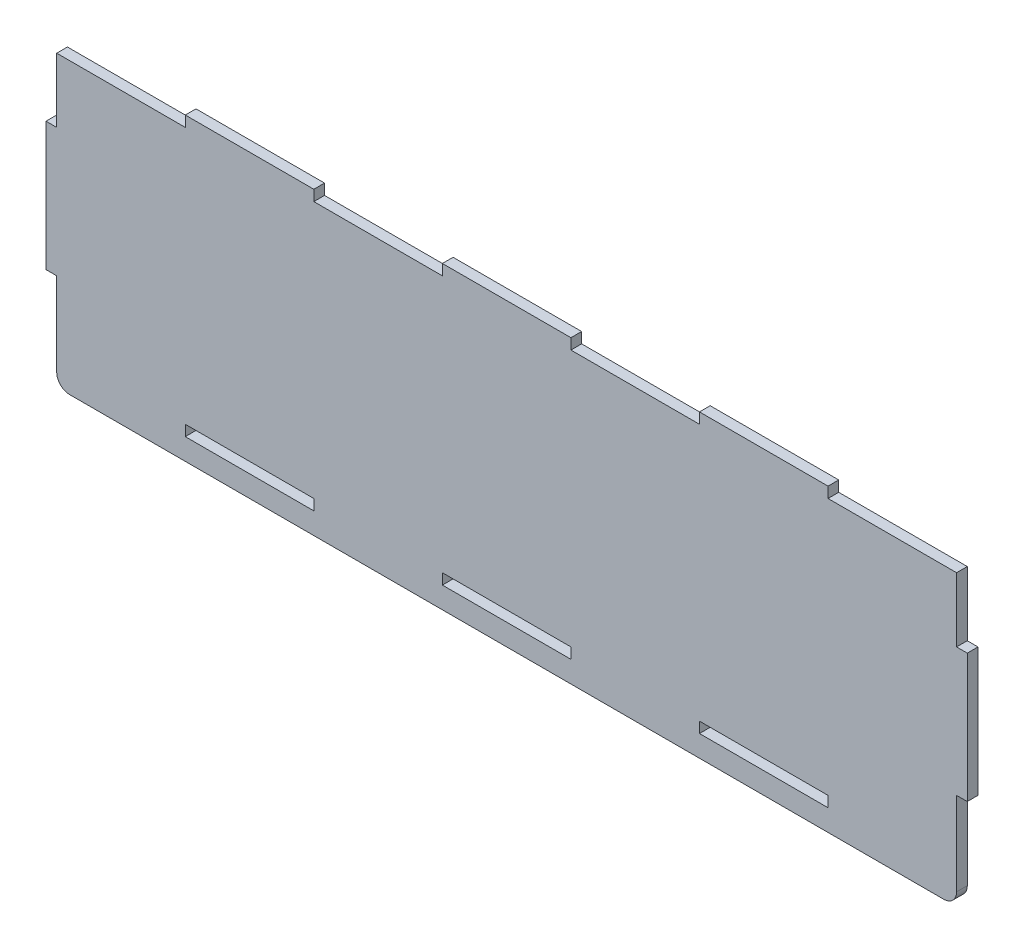
SolidWorks part; units mm, degrees
material "Maple"
ref_plane "Front Plane" through (0, 0, 0) normal (0, 0, 1) x (1, 0, 0)
ref_plane "Top Plane" through (0, 0, 0) normal (0, 1, 0) x (1, 0, 0)
ref_plane "Right Plane" through (0, 0, 0) normal (1, 0, 0) x (0, 0, -1)
sketch "Sketch1" plane through (0, 0, 0) normal (0, 0, 1) x (1, 0, 0)
  line L0 (107.5, 0) -> (-107.5, 0) construction
  line L1 (-107.5, -32.5) -> (107.5, -32.5) construction
  line L2 (-107.5, -32.5) -> (-107.5, 32.5) construction
  line L3 (-107.5, 32.5) -> (107.5, 32.5) construction
  line L4 (107.5, -32.5) -> (107.5, 32.5) construction
  line L5 (-107.5, -32.5) -> (107.5, 32.5) construction
  line L6 (-107.5, 32.5) -> (107.5, -32.5) construction
  line L7 (-107.5, 30) -> (107.5, 30) construction
  line L8 (105, 32.5) -> (105, -32.5) construction
  line L9 (-107.5, -30) -> (107.5, -30) construction
  line L10 (0, 32.5) -> (0, -32.5) construction
  line L11 (-105, 32.5) -> (-105, -32.5) construction
  line L12 (-75, 30) -> (-105, 30)
  line L13 (-75, 30) -> (-75, 32.5)
  line L14 (-75, 32.5) -> (-45, 32.5)
  line L15 (-45, 32.5) -> (-45, 30)
  line L16 (-45, 30) -> (-15, 30)
  line L17 (-15, 30) -> (-15, 32.5)
  line L18 (-15, 32.5) -> (15, 32.5)
  line L19 (15, 30) -> (15, 32.5)
  line L20 (45, 30) -> (15, 30)
  line L21 (45, 32.5) -> (45, 30)
  line L22 (75, 32.5) -> (45, 32.5)
  line L23 (75, 30) -> (75, 32.5)
  line L24 (75, 30) -> (105, 30)
  line L25 (-75, -30) -> (-105, -30) construction
  line L26 (-75, -30) -> (-75, -32.5)
  line L27 (-75, -32.5) -> (-45, -32.5) construction
  line L28 (-45, -32.5) -> (-45, -30)
  line L29 (-45, -30) -> (-15, -30) construction
  line L30 (-15, -30) -> (-15, -32.5)
  line L31 (-15, -32.5) -> (15, -32.5) construction
  line L32 (15, -30) -> (15, -32.5)
  line L33 (45, -30) -> (15, -30) construction
  line L34 (45, -32.5) -> (45, -30)
  line L35 (75, -32.5) -> (45, -32.5) construction
  line L36 (75, -30) -> (75, -32.5)
  line L37 (75, -30) -> (105, -30) construction
  line L38 (-105, 30) -> (-105, 15)
  line L39 (-105, 15) -> (-107.5, 15)
  line L40 (-107.5, 15) -> (-107.5, -15)
  line L41 (-105, -30) -> (-105, -15)
  line L42 (-105, -15) -> (-107.5, -15)
  line L43 (105, -30) -> (105, -15)
  line L44 (105, 30) -> (105, 15)
  line L45 (107.5, 15) -> (107.5, -15)
  line L46 (105, 15) -> (107.5, 15)
  line L47 (105, -15) -> (107.5, -15)
  line L53 (-75, -32.5) -> (-45, -32.5) construction
  line L59 (-105, -30) -> (105, 30) construction
  line L60 (-105, 30) -> (105, -30) construction
  line L65 (-107.5, -30) -> (107.5, 30) construction
  line L66 (-107.5, 30) -> (107.5, -30) construction
  line L69 (-15, -32.5) -> (15, -32.5) construction
  line L73 (45, -32.5) -> (75, -32.5) construction
  line L76 (-75, -30) -> (-45, -30)
  line L77 (105, -30) -> (105, -37.5)
  line L78 (105, -37.5) -> (-105, -37.5)
  line L79 (-105, -37.5) -> (-105, -30)
  line L80 (-75, -32.5) -> (-45, -32.5)
  line L82 (-15, -32.5) -> (15, -32.5)
  line L83 (45, -32.5) -> (75, -32.5)
  line L84 (-15, -30) -> (15, -30)
  line L85 (45, -30) -> (75, -30)
  point P0 (0, 0)
  point P54 (0, 0)
  point P59 (0, 0)
  point P60 (0, 0)
  dimension "D1" = 2.5
  dimension "D2" = 2.5
  dimension "D3" = 65
  dimension "D4" = 215
  dimension "D5" = 30
  dimension "D6" = 5
extrude "Boss-Extrude1" add sketch "Sketch1" along normal mid plane 2.5 contours L79 L78 L77 L43 L47 L45 L46 L44 L24 L23 L22 L21 L20 L19 L18 L17 L16 L15 L14 L13 L12 L38 L39 L40 L42 L41 L80 L26 L76 L28 L30 L84 L32 L82 L34 L85 L36 L83
sketch "Sketch2" [suppressed] plane through (0, 0, 1.25) normal (0, 0, 1) x (1, 0, 0)
  line L0 (-42, 7) -> (-42, 13)
  line L1 (83, -22.325) -> (95, -22.325)
  line L2 (83, -22.325) -> (83, 1.675)
  line L3 (83, 1.675) -> (95, 1.675)
  line L4 (95, -22.325) -> (95, 1.675)
  line L5 (83, -22.325) -> (95, 1.675) construction
  line L6 (83, 1.675) -> (95, -22.325) construction
  line L7 (107.5, 0) -> (-107.5, 0) construction
  line L8 (-68, 7) -> (-62, 7)
  line L9 (-68, 7) -> (-68, 13)
  line L10 (-68, 13) -> (-62, 13)
  line L11 (-94.5, -15.325) -> (-93.86, -15.325)
  line L12 (-62, 7) -> (-62, 13)
  line L13 (-94.5, -22.325) -> (-85.5, -22.325)
  line L14 (-94.5, -22.325) -> (-94.5, -15.325)
  line L15 (-94.5, -15.325) -> (-85.5, -15.325) construction
  line L16 (-85.5, -22.325) -> (-85.5, -15.325)
  line L17 (-94.5, -22.325) -> (-85.5, -15.325) construction
  line L18 (-94.5, -15.325) -> (-85.5, -22.325) construction
  line L19 (-5.08, -18.165) -> (5.08, -18.165)
  line L20 (-5.08, -18.165) -> (-5.08, -15.625)
  line L21 (-5.08, -15.625) -> (5.08, -15.625)
  line L22 (5.08, -18.165) -> (5.08, -15.625)
  line L23 (-5.08, -18.165) -> (5.08, -15.625) construction
  line L24 (-5.08, -15.625) -> (5.08, -18.165) construction
  line L25 (-86.14, -15.325) -> (-85.5, -15.325)
  line L30 (-6.07, 14.025) -> (6.07, 19.775) construction
  line L31 (-6.07, 19.775) -> (6.07, 14.025) construction
  line L32 (6.07, 19.775) -> (6.07, 14.025)
  line L33 (-6.07, 14.025) -> (6.07, 14.025)
  line L34 (-6.07, 19.775) -> (-6.07, 14.025)
  line L35 (-6.07, 19.775) -> (6.07, 19.775)
  line L36 (-105, 30) -> (-105, 15) construction
  line L37 (107.5, 15) -> (107.5, -15) construction
  line L38 (-75, -30) -> (-45, -30) construction
  line L39 (-68, 7) -> (-62, 13) construction
  line L40 (-68, 13) -> (-62, 7) construction
  line L41 (-42, 7) -> (-36, 7)
  line L42 (-36, 7) -> (-36, 13)
  line L43 (-42, 13) -> (-36, 13)
  circle A0 centre (-90, 10) radius 5.85
  circle A2 centre (-65, -16.895) radius 6
  circle A3 centre (-90, -5) radius 2.5
  arc A4 (-93.86, -15.325) -> (-86.14, -15.325) centre (-90, -15.325) cw
  circle A5 centre (-65, -5) radius 2.5
  circle A6 centre (89, 10) radius 2.5
  point P0 (89, -10.325)
  point P5 (-65, 10)
  point P12 (0, -16.895)
  point P13 (-90, -18.825)
  point P45 (0, 16.9)
  dimension "D4" = 11.7
  dimension "D5" = 12
  dimension "D9" = 5
  dimension "D12" = 3.86
  dimension "D1" = 12
  dimension "D2" = 24
  dimension "D3" = 12.5
  dimension "D6" = 15
  dimension "D7" = 9
  dimension "D8" = 1.93
  dimension "D10" = 5
  dimension "D11" = 7
  dimension "D13" = 11.175
  dimension "D14" = 25
  dimension "D15" = 2.54
  dimension "D16" = 10.16
  dimension "D17" = 12.14
  dimension "D18" = 5.75
  dimension "D19" = 16.9
  dimension "D20" = 16.895
  dimension "D21" = 6
  dimension "D23" = 20
  dimension "D24" = 10
  dimension "D22" = 2
extrude "Cut-Extrude1" [suppressed] cut sketch "Sketch2" against normal blind 10 contours A5 | A6
ref_point "Point1" [suppressed]
ref_point "Point2" [suppressed]
ref_point "Point3" [suppressed]
sketch "Sketch3" [suppressed] plane through (0, 0, 1.25) normal (0, 0, 1) x (1, 0, 0)
  line L0 (-98.0553, 21.2087) -> (-81.9447, 21.2087) construction
  line L1 (-76.0925, 21.2087) -> (-53.9075, 21.2087) construction
  line L2 (75.2582, 21.2087) -> (102.7418, 21.2087) construction
  line L3 (-11.8929, -13.625) -> (11.8929, -13.625) construction
  line L4 (-46.0729, 21.2087) -> (-30.0977, 21.2087) construction
  line L5 (-4.81, -20.165) -> (-4.81, -25.8363) construction
  line L7 (-2.27, -20.165) -> (-2.27, -25.8363) construction
  line L8 (0.27, -20.165) -> (0.27, -25.8363) construction
  line L9 (2.81, -20.165) -> (2.81, -25.8363) construction
  line L10 (-25.0112, 21.775) -> (25.0112, 21.775) construction
  line L11 (-5.08, -15.625) -> (-5.08, -18.165) construction
  line L12 (-21.372, 0) -> (43.5989, 0) construction
  line L13 (-4.81, 12.025) -> (-4.81, 5.0863) construction
  line L14 (-2.27, 12.025) -> (-2.27, 5.0863) construction
  line L15 (0.27, 12.025) -> (0.27, 5.0863) construction
  line L16 (2.81, 12.025) -> (2.81, 5.0863) construction
  line L19 (6.07, 19.775) -> (-6.07, 19.775) construction
  line L20 (-6.07, 14.025) -> (6.07, 14.025) construction
  line L21 (5.08, -15.625) -> (-5.08, -15.625) construction
  line L22 (-5.08, -18.165) -> (5.08, -18.165) construction
  text T0 "12V\r\n" font "Clarendon BT" height 5
  text T1 "Active" font "Clarendon BT" height 5
  text T2 "PUMP" font "Clarendon BT" height 5
  text T3 "USB-TTL" font "Century Gothic" height 5
  text T4 "5V" font "Century Gothic" height 2
  text T5 "TX\r\n" font "Century Gothic" height 2
  text T6 "RX" font "Century Gothic" height 2
  text T7 "GND" font "Century Gothic" height 2
  text T8 "HC-SR04" font "Clarendon BT" height 5
  text T9 "VCC" font "Century Gothic" height 2
  text T10 "TRIG" font "Century Gothic" height 2
  text T11 "ECHO\r\n" font "Century Gothic" height 2
  text T12 "GND" font "Century Gothic" height 2
  text T13 "RST" font "Clarendon BT" height 5
  point P2 (-90, 21.2087)
  point P7 (-65, 21.2087)
  point P10 (89, 21.2087)
  point P57 (0, 21.775)
  dimension "D1" = 4
  dimension "D2" = 0.27
  dimension "D3" = 2.54
  dimension "D4" = 2
  dimension "D5" = 2
  dimension "D7" = 2
  dimension "D8" = 2
  dimension "D6" = 4
extrude "Cut-Extrude2" [suppressed] cut sketch "Sketch3" against normal blind 1
fillet "Fillet1" radius 3 2 edges at (105, -37.5, 0) (-105, -37.5, 0)
